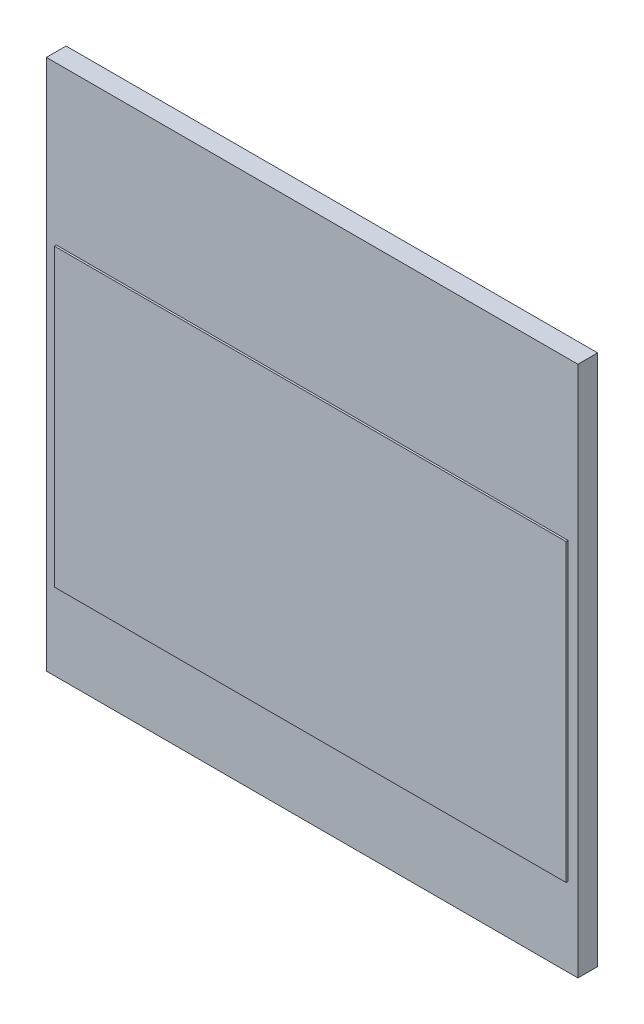
SolidWorks part; units mm, degrees
ref_plane "Front Plane" through (0, 0, 0) normal (0, 0, 1) x (1, 0, 0)
ref_plane "Top Plane" through (0, 0, 0) normal (0, 1, 0) x (1, 0, 0)
ref_plane "Right Plane" through (0, 0, 0) normal (1, 0, 0) x (0, 0, -1)
sketch "Sketch1" plane through (0, 0, 0) normal (0, 0, 1) x (1, 0, 0)
  line L1 (-13, -7.5) -> (13, -7.5)
  line L2 (-13, -7.5) -> (-13, 7.5)
  line L3 (-13, 7.5) -> (13, 7.5)
  line L4 (13, -7.5) -> (13, 7.5)
  line L5 (-13, -7.5) -> (13, 7.5) construction
  line L6 (-13, 7.5) -> (13, -7.5) construction
  point P0 (0, 0)
  dimension "D1" = 26
  dimension "D2" = 15
extrude "Boss-Extrude1" add sketch "Sketch1" along normal blind 0.1
sketch "Sketch2" plane through (0, 0, 0) normal (0, 0, -1) x (-1, 0, 0)
  line L1 (-13.5, -11.5) -> (13.5, -11.5)
  line L2 (-13.5, -11.5) -> (-13.5, 15.5)
  line L3 (-13.5, 15.5) -> (13.5, 15.5)
  line L4 (13.5, -11.5) -> (13.5, 15.5)
  line L5 (-13.5, -11.5) -> (13.5, 15.5) construction
  line L6 (-13.5, 15.5) -> (13.5, -11.5) construction
  line L7 (13, -7.5) -> (-13, -7.5) construction
  line L9 (-13, -7.5) -> (-13, 7.5) construction
  point P0 (1, 1)
  dimension "D1" = 27
  dimension "D2" = 27
  dimension "D3" = 4
  dimension "D4" = 0.5
extrude "Boss-Extrude2" add sketch "Sketch2" along normal blind 1
